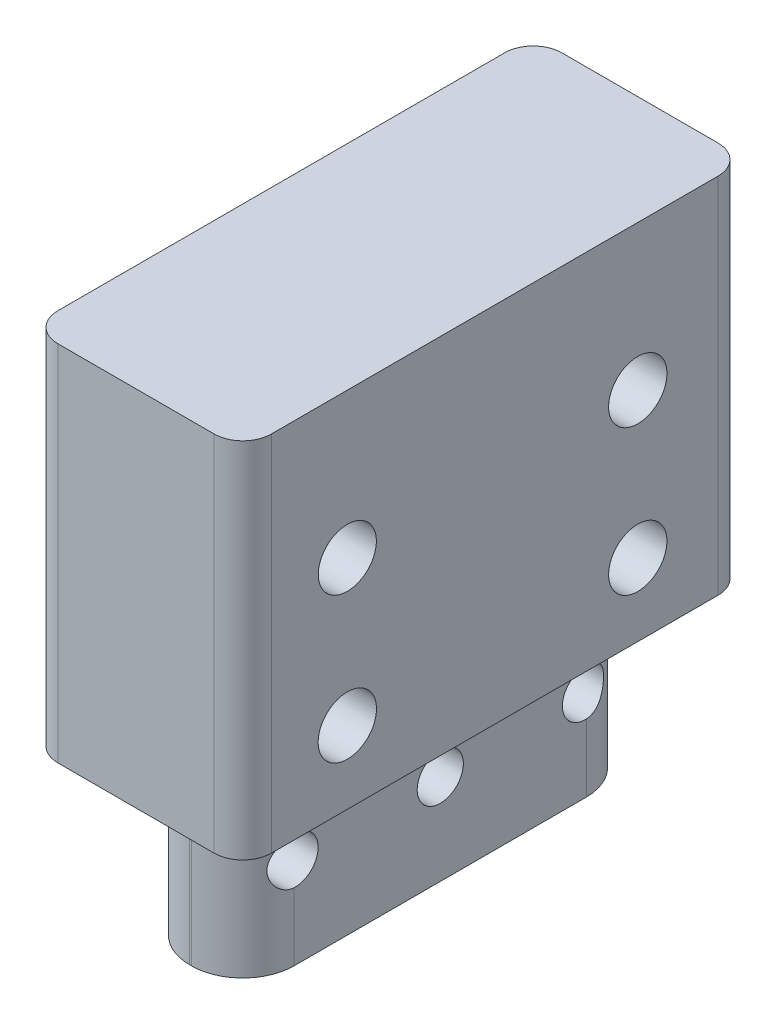
SolidWorks part; units mm, degrees
material "6061-T6 (SS)"
ref_plane "Front Plane" through (0, 0, 0) normal (0, 0, 1) x (1, 0, 0)
ref_plane "Top Plane" through (0, 0, 0) normal (0, 1, 0) x (1, 0, 0)
ref_plane "Right Plane" through (0, 0, 0) normal (1, 0, 0) x (0, 0, -1)
sketch "Sketch1" plane through (0, 0, 0) normal (0, 0, 1) x (1, 0, 0)
  line L1 (0, 0) -> (18.669, 0)
  line L2 (0, 0) -> (0, 50.8)
  line L3 (0, 50.8) -> (18.669, 50.8)
  line L4 (18.669, 0) -> (18.669, 50.8)
  dimension "D1" = 50.8
  dimension "D2" = 18.669
extrude "Boss-Extrude1" add sketch "Sketch1" along normal blind 44.069
sketch "Sketch2" plane through (18.669, 0, 0) normal (1, 0, 0) x (0, 0, -1)
  line L0 (-44.069, 0) -> (-44.069, 50.8) construction
  line L1 (0, 0) -> (-44.069, 0)
  line L2 (0, 0) -> (0, 4.7625)
  line L3 (0, 4.7625) -> (-44.069, 4.7625)
  line L4 (-44.069, 0) -> (-44.069, 4.7625)
  dimension "D1" = 4.7625
extrude "Cut-Extrude1" cut sketch "Sketch2" against normal through all
sketch "Sketch3" plane through (18.669, 0, 0) normal (1, 0, 0) x (0, 0, -1)
  line L0 (-44.069, 4.7625) -> (-44.069, 50.8) construction
  line L1 (0, 4.7625) -> (-44.069, 4.7625)
  line L2 (0, 4.7625) -> (0, 19.0525)
  line L3 (0, 19.0525) -> (-44.069, 19.0525)
  line L4 (-44.069, 4.7625) -> (-44.069, 19.0525)
  dimension "D1" = 14.29
sketch "Sketch4" plane through (0, 0, 44.069) normal (0, 0, 1) x (1, 0, 0)
  line L0 (18.669, 4.7625) -> (18.669, 19.0525) construction
  line L1 (18.669, 19.0525) -> (0, 19.0525)
  line L2 (18.669, 19.0525) -> (18.669, 4.7625)
  line L3 (18.669, 4.7625) -> (0, 4.7625)
  line L4 (0, 19.0525) -> (0, 4.7625)
  line L5 (18.669, 4.7625) -> (18.669, 50.8) construction
  dimension "D1" = 14.29
sketch "Sketch5" plane through (0, 0, 0) normal (-1, 0, 0) x (0, 0, 1)
  line L1 (44.069, 19.0525) -> (0, 19.0525)
  line L2 (44.069, 19.0525) -> (44.069, 4.7625)
  line L3 (44.069, 4.7625) -> (0, 4.7625)
  line L4 (0, 19.0525) -> (0, 4.7625)
sketch "Sketch6" plane through (0, 0, 0) normal (0, 0, -1) x (-1, 0, 0)
  line L1 (0, 19.0525) -> (-18.669, 19.0525)
  line L2 (0, 19.0525) -> (0, 4.7625)
  line L3 (0, 4.7625) -> (-18.669, 4.7625)
  line L4 (-18.669, 19.0525) -> (-18.669, 4.7625)
extrude "Cut-Extrude2" cut sketch "Sketch3" against normal blind 4.7625
extrude "Cut-Extrude3" cut sketch "Sketch5" against normal blind 4.7625
extrude "Cut-Extrude4" cut sketch "Sketch4" against normal blind 4.7625
extrude "Cut-Extrude5" cut sketch "Sketch6" against normal blind 4.7625
fillet "Fillet1" radius 4.5009 4 edges at (4.7625, 11.9075, 39.3065) (13.9065, 11.9075, 39.3065) (4.7625, 11.9075, 4.7625) (13.9065, 11.9075, 4.7625)
fillet "Fillet2" radius 2.4994 4 edges at (0, 34.9263, 44.069) (18.669, 34.9263, 44.069) (18.669, 34.9263, 0) (0, 34.9263, 0)
sketch "Sketch7" plane through (0, 0, 0) normal (-1, 0, 0) x (0, 0, 1)
  line L0 (41.5696, 50.8) -> (2.4994, 50.8) construction
  line L1 (2.4994, 50.8) -> (2.4994, 19.0525) construction
  line L2 (41.5696, 19.0525) -> (41.5696, 50.8) construction
  line L3 (41.5696, 19.0525) -> (2.4994, 19.0525) construction
  circle A0 centre (9.5259, 38.1) radius 2.5527
  circle A1 centre (34.9259, 38.1) radius 2.54
  circle A2 centre (34.9259, 25.4) radius 2.5527
  circle A3 centre (9.5259, 25.4) radius 2.5527
  point P12 (0, 0)
  point P13 (0, 0)
  point P15 (0, 0)
  point P16 (0, 0)
  dimension "D1" = 25.4
  dimension "D2" = 12.7
  dimension "D3" = 5.1054
  dimension "D4" = 7.0265
  dimension "D5" = 6.6438
  dimension "D6" = 5.08
  dimension "D7" = 5.1054
  dimension "D8" = 7.0265
  dimension "D9" = 6.3475
  dimension "D10" = 25.4
  dimension "D11" = 5.1054
  dimension "D12" = 6.6438
extrude "Cut-Extrude6" cut sketch "Sketch7" against normal through all
sketch "Sketch8" plane through (4.7625, 0, 0) normal (-1, 0, 0) x (0, 0, 1)
  line L0 (9.2634, 4.7625) -> (34.8056, 4.7625) construction
  line L2 (9.2634, 19.0525) -> (9.2634, 4.7625) construction
  circle A0 centre (22.0354, 12.7) radius 2.0193
  circle A1 centre (34.7354, 12.7) radius 2.0193
  circle A2 centre (9.3354, 12.7) radius 2.0193
  point P9 (0, 0)
  point P10 (0, 0)
  dimension "D1" = 4.0386
  dimension "D2" = 4.0386
  dimension "D3" = 4.0386
  dimension "D4" = 7.9375
  dimension "D5" = 12.7
  dimension "D6" = 7.9375
  dimension "D7" = 12.772
  dimension "D8" = 12.7
  dimension "D9" = 7.9375
extrude "Cut-Extrude7" cut sketch "Sketch8" against normal through all
